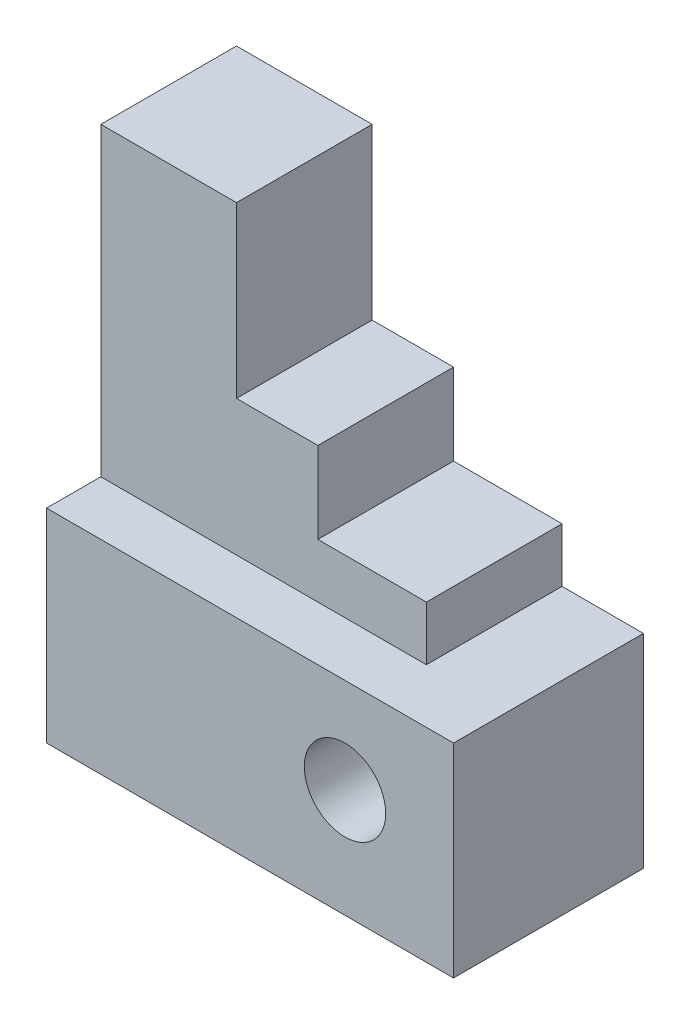
SolidWorks part; units mm, degrees
material "Aluminum Bronze"
ref_plane "Front Plane" through (0, 0, 0) normal (0, 0, 1) x (1, 0, 0)
ref_plane "Top Plane" through (0, 0, 0) normal (0, 1, 0) x (1, 0, 0)
ref_plane "Right Plane" through (0, 0, 0) normal (1, 0, 0) x (0, 0, -1)
sketch "Sketch1" plane through (0, 0, 0) normal (0, 0, 1) x (1, 0, 0)
  line L1 (0, 0) -> (60, 0)
  line L2 (0, 0) -> (0, 30)
  line L3 (0, 30) -> (60, 30)
  line L4 (60, 0) -> (60, 30)
  circle A0 centre (44, 16) radius 6
  dimension "D3" = 12
  dimension "D5" = 16
  dimension "D1" = 30
  dimension "D2" = 60
  dimension "D4" = 16
extrude "Boss-Extrude1" add sketch "Sketch1" along normal blind 28
sketch "Sketch2" plane through (0, 0, 0) normal (0, 0, 1) x (1, 0, 0)
  line L0 (0, 30) -> (0, 75)
  line L1 (0, 75) -> (20, 75)
  line L2 (20, 75) -> (20, 50)
  line L3 (20, 50) -> (32, 50)
  line L4 (32, 50) -> (32, 38)
  line L5 (32, 38) -> (48, 38)
  line L6 (48, 38) -> (48, 30)
  line L7 (60, 30) -> (0, 30) construction
  line L8 (48, 30) -> (0, 30)
  line L9 (60, 0) -> (60, 30) construction
  line L10 (0, 0) -> (60, 0) construction
  dimension "D1" = 20
  dimension "D2" = 12
  dimension "D3" = 12
  dimension "D4" = 12
  dimension "D5" = 20
  dimension "D6" = 75
extrude "Boss-Extrude2" add sketch "Sketch2" along normal blind 20
